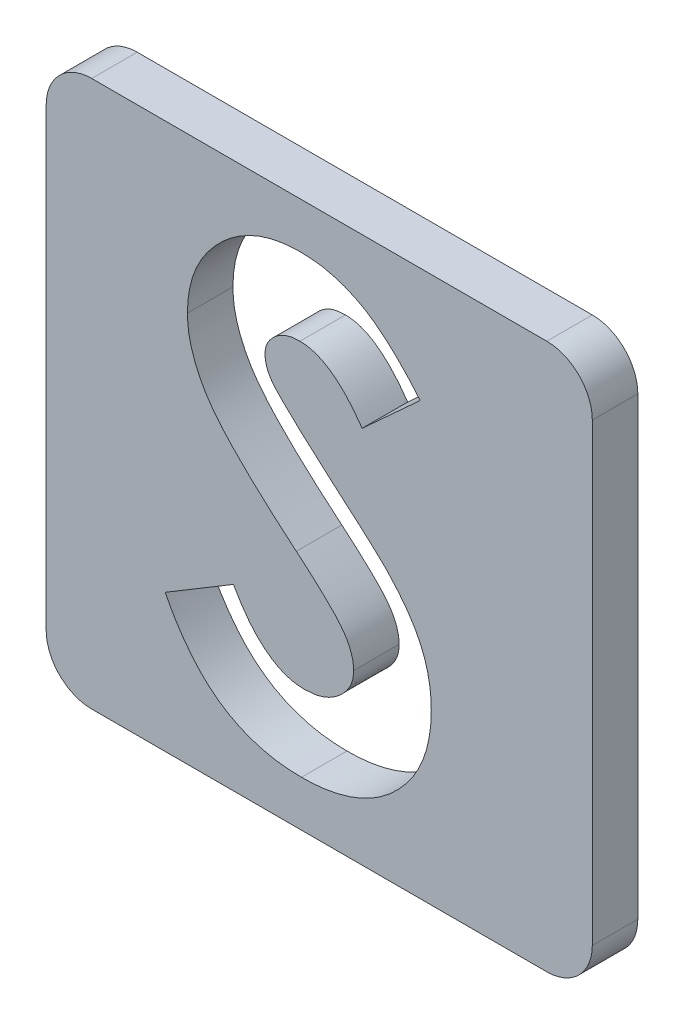
SolidWorks part; units mm, degrees
ref_plane "Front Plane" through (0, 0, 0) normal (0, 0, 1) x (1, 0, 0)
ref_plane "Top Plane" through (0, 0, 0) normal (0, 1, 0) x (1, 0, 0)
ref_plane "Right Plane" through (0, 0, 0) normal (1, 0, 0) x (0, 0, -1)
sketch "Sketch1" plane through (0, 0, 0) normal (0, 0, 1) x (1, 0, 0)
  line L1 (-50, 60) -> (50, 60)
  line L2 (-60, 50) -> (-60, -50)
  line L3 (-50, -60) -> (50, -60)
  line L4 (60, 50) -> (60, -50)
  line L5 (-60, 60) -> (60, -60) construction
  line L6 (-60, -60) -> (60, 60) construction
  arc A0 (-60, -50) -> (-50, -60) centre (-50, -50) ccw
  arc A1 (50, -60) -> (60, -50) centre (50, -50) ccw
  arc A2 (50, 60) -> (60, 50) centre (50, 50) cw
  arc A3 (-50, 60) -> (-60, 50) centre (-50, 50) ccw
  point P0 (0, 0)
  dimension "D3" = 10
  dimension "D1" = 120
  dimension "D2" = 120
extrude "Boss-Extrude1" add sketch "Sketch1" along normal blind 10 contours A3 L2 A0 L3 A1 L4 A2 L1
sketch "Sketch2" plane through (0, 0, 10) normal (0, 0, 1) x (1, 0, 0)
  line L0 (0, 0) -> (0, 40) construction
  line L1 (-50, 50) -> (50, 50) construction
  line L2 (-50, 50) -> (-50, -50) construction
  line L3 (-50, -50) -> (50, -50) construction
  line L4 (50, 50) -> (50, -50) construction
  line L5 (-50, 50) -> (50, -50) construction
  line L6 (-50, -50) -> (50, 50) construction
  line L7 (0, 40) -> (-40, 40) construction
  line L8 (-40, 40) -> (-40, 0) construction
  line L9 (-40, 0) -> (0, 0) construction
  line L11 (0, 20) -> (-20, 20) construction
  line L12 (-20, 40) -> (-20, 20) construction
  circle A0 centre (0, 40) radius 4 construction
  circle A1 centre (0, 20) radius 4 construction
  circle A2 centre (0, 0) radius 4 construction
  circle A3 centre (-20, 20) radius 4 construction
  circle A4 centre (-20, 40) radius 4 construction
  circle A5 centre (-40, 40) radius 4 construction
  circle A6 centre (0, 0) radius 4 construction
  circle A7 centre (20, 0) radius 4 construction
  circle A8 centre (40, 0) radius 4 construction
  circle A9 centre (40, 20) radius 4 construction
  circle A10 centre (40, 40) radius 4 construction
  circle A11 centre (20, 20) radius 4 construction
  circle A12 centre (0, 0) radius 4 construction
  circle A13 centre (0, -20) radius 4 construction
  circle A14 centre (0, -40) radius 4 construction
  circle A15 centre (20, -40) radius 4 construction
  circle A16 centre (40, -40) radius 4 construction
  circle A17 centre (20, -20) radius 4 construction
  circle A18 centre (0, 0) radius 4 construction
  circle A19 centre (-20, 0) radius 4 construction
  circle A20 centre (-40, 0) radius 4 construction
  circle A21 centre (-40, -20) radius 4 construction
  circle A22 centre (-40, -40) radius 4 construction
  circle A23 centre (-20, -20) radius 4 construction
  text T0 "S" font "Century Gothic" height 95
  point P0 (0, 0)
  point P55 (0, 0)
  dimension "D4" = 8
  dimension "D1" = 100
  dimension "D2" = 100
  dimension "D3" = 40
  dimension "D5" = 4
extrude "Cut-Extrude32" cut sketch "Sketch2" against normal blind 10
